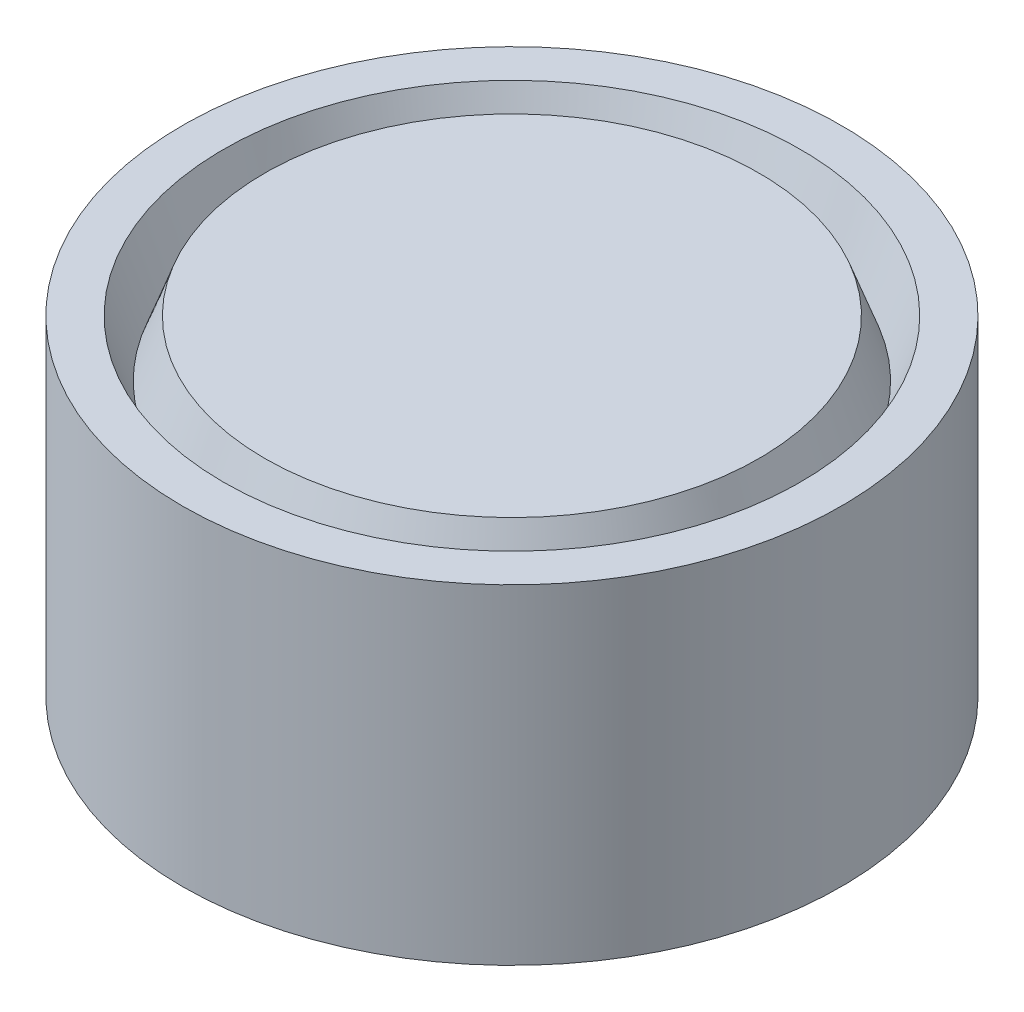
SolidWorks part; units mm, degrees
ref_plane "Front Plane" through (0, 0, 0) normal (0, 0, 1) x (1, 0, 0)
ref_plane "Top Plane" through (0, 0, 0) normal (0, 1, 0) x (1, 0, 0)
ref_plane "Right Plane" through (0, 0, 0) normal (1, 0, 0) x (0, 0, -1)
sketch "Sketch1" plane through (0, 0, 0) normal (0, 1, 0) x (1, 0, 0)
  circle A0 centre (0, 0) radius 20
  dimension "D1" = 40
extrude "Boss-Extrude1" add sketch "Sketch1" along normal blind 20
sketch "Sketch2" plane through (0, 20, 0) normal (0, 1, 0) x (1, 0, 0)
  circle A0 centre (0, 0) radius 17.5
  circle A1 centre (0, 0) radius 15
  dimension "D1" = 30
  dimension "D2" = 35
extrude "Cut-Extrude1" cut sketch "Sketch2" against normal blind 10 draft 20
sketch "Sketch3" plane through (0, 0, 0) normal (0, -1, 0) x (1, 0, 0)
  circle A0 centre (0, 0) radius 2
  dimension "D1" = 4
extrude "Cut-Extrude2" cut sketch "Sketch3" against normal blind 5
